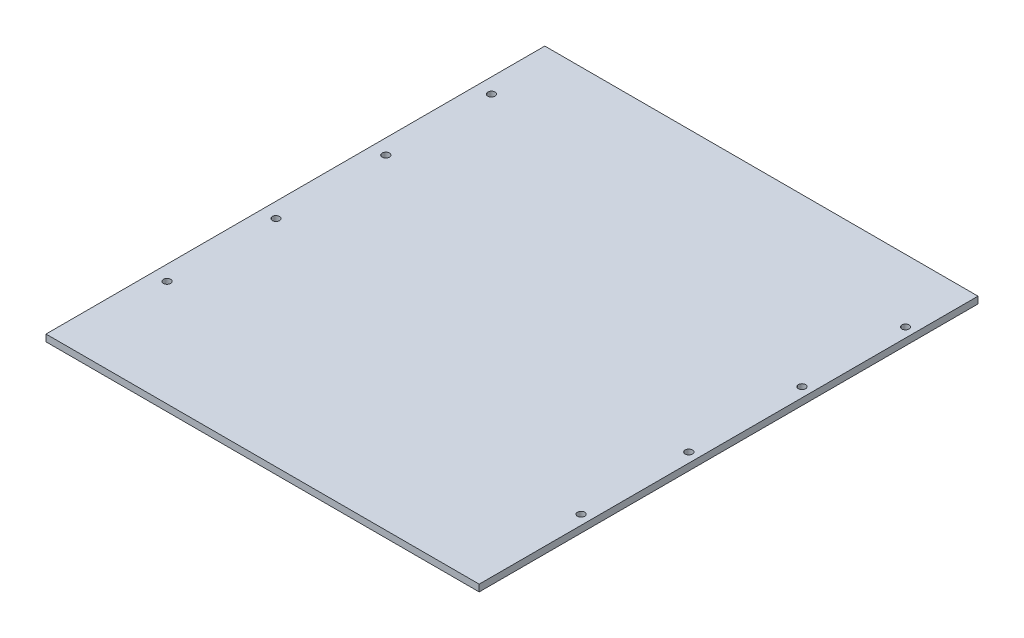
SolidWorks part; units mm, degrees
ref_plane "Front Plane" through (0, 0, 0) normal (0, 0, 1) x (1, 0, 0)
ref_plane "Top Plane" through (0, 0, 0) normal (0, 1, 0) x (1, 0, 0)
ref_plane "Right Plane" through (0, 0, 0) normal (1, 0, 0) x (0, 0, -1)
sketch "Sketch1" plane through (0, 0, 0) normal (0, 1, 0) x (1, 0, 0)
  line L1 (0, 0) -> (203, 0)
  line L2 (0, 0) -> (0, 238)
  line L3 (0, 238) -> (203, 238)
  line L4 (203, 0) -> (203, 238)
  dimension "D1" = 203
  dimension "D2" = 238
extrude "Boss-Extrude1" add sketch "Sketch1" along normal blind 3.175
sketch "Sketch2" plane through (0, 3.175, 0) normal (0, 1, 0) x (1, 0, 0)
  line L0 (7, 238) -> (7, 206) construction
  line L1 (203, 238) -> (0, 238) construction
  line L2 (7, 206) -> (0, 206) construction
  line L3 (0, 238) -> (0, 0) construction
  line L4 (7, 206) -> (7, 156.5) construction
  line L5 (7, 156.5) -> (7, 105) construction
  line L6 (7, 105) -> (7, 54) construction
  circle A0 centre (7, 206) radius 1.7
  circle A1 centre (7, 156.5) radius 1.7
  circle A2 centre (7, 105) radius 1.7
  circle A3 centre (7, 54) radius 1.7
  dimension "D3" = 3.4
  dimension "D1" = 32
  dimension "D2" = 7
  dimension "D4" = 49.5
  dimension "D5" = 51.5
  dimension "D6" = 51
extrude "Cut-Extrude1" cut sketch "Sketch2" against normal through all
sketch "Sketch3" plane through (0, 3.175, 0) normal (0, 1, 0) x (1, 0, 0)
  line L0 (198.5, 238) -> (198.5, 208.5) construction
  line L1 (203, 238) -> (0, 238) construction
  line L2 (198.5, 208.5) -> (203, 208.5) construction
  line L3 (203, 0) -> (203, 238) construction
  line L4 (198.5, 208.5) -> (198.5, 160) construction
  line L5 (198.5, 160) -> (198.5, 107) construction
  line L6 (198.5, 107) -> (198.5, 56.5) construction
  circle A0 centre (198.5, 208.5) radius 1.7
  circle A1 centre (7, 206) radius 1.7 construction
  circle A2 centre (198.5, 160) radius 1.7
  circle A3 centre (198.5, 107) radius 1.7
  circle A4 centre (198.5, 56.5) radius 1.7
  dimension "D3" = 48.5
  dimension "D1" = 29.5
  dimension "D2" = 4.5
  dimension "D4" = 53
  dimension "D5" = 50.5
extrude "Cut-Extrude2" cut sketch "Sketch3" against normal through all
sketch "Sketch4" plane through (0, 3.175, 0) normal (0, 1, 0) x (1, 0, 0)
  line L0 (203, 0) -> (203, 238) construction
  line L1 (0, 0) -> (203, 0)
  line L2 (0, 0) -> (0, 4.25)
  line L3 (0, 4.25) -> (203, 4.25)
  line L4 (203, 0) -> (203, 4.25)
  dimension "D1" = 4.25
extrude "Cut-Extrude3" cut sketch "Sketch4" against normal through all
